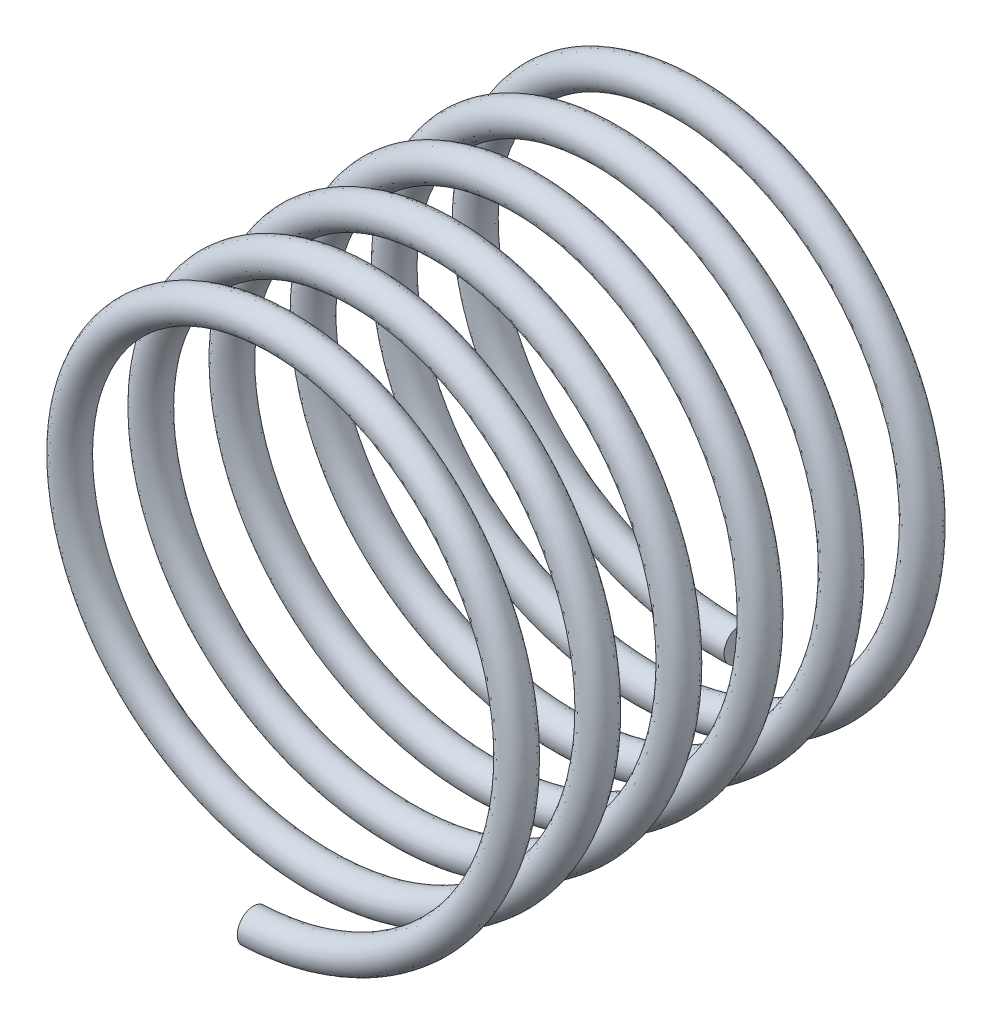
SolidWorks part; units mm, degrees
ref_plane "Front Plane" through (0, 0, 0) normal (1, 0, 0) x (0, 1, 0)
ref_plane "Top Plane" through (0, 0, 0) normal (0, 0, 1) x (0, 1, 0)
ref_plane "Right Plane" through (0, 0, 0) normal (0, 1, 0) x (-1, 0, 0)
sketch "Sketch2" plane through (0, 0, 0) normal (0, 0, 1) x (0, 1, 0)
  circle A0 centre (0, 0) radius 1.5
  dimension "D1" = 3
curve "Helix/Spiral1" pitch 0.5 height 3 turns 6
sweep "Sweep1" add path "Helix/Spiral1" circular profile diameter 0.2 parameters "D3"=0.2
